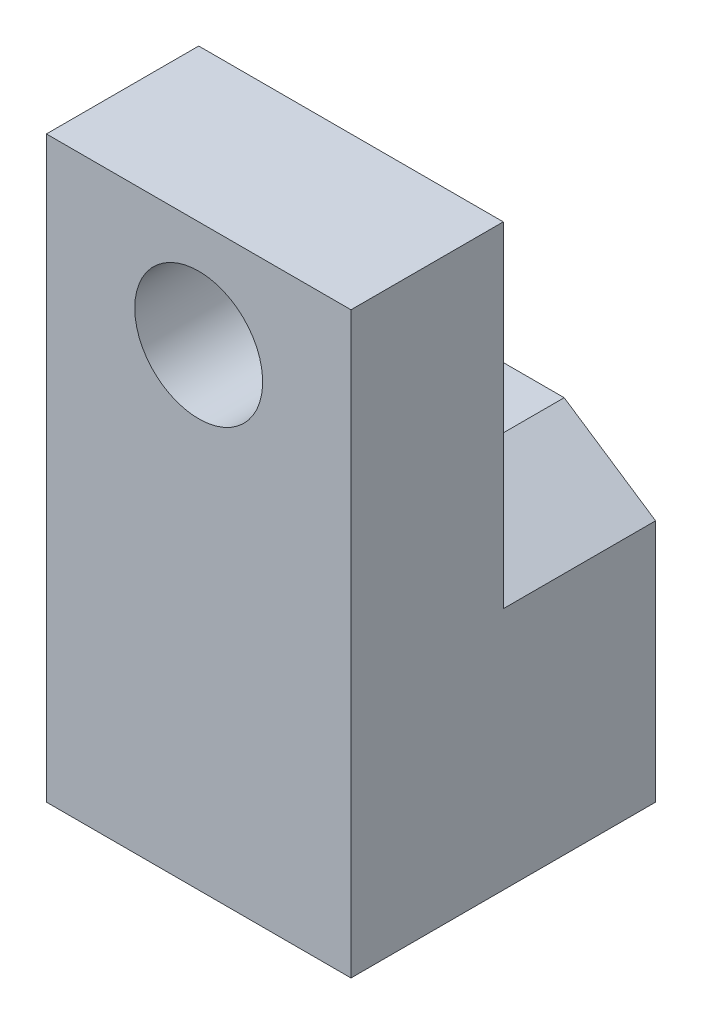
SolidWorks part; units mm, degrees
material "POM 乙缩醛共聚物"
ref_plane "前视基准面" through (0, 0, 0) normal (0, 0, 1) x (1, 0, 0)
ref_plane "上视基准面" through (0, 0, 0) normal (0, 1, 0) x (1, 0, 0)
ref_plane "右视基准面" through (0, 0, 0) normal (1, 0, 0) x (0, 0, -1)
sketch "草图1" plane through (0, 0, 0) normal (0, 0, 1) x (1, 0, 0)
  line L1 (-5, 9.5) -> (5, 9.5)
  line L2 (-5, 9.5) -> (-5, -9.5)
  line L3 (-5, -9.5) -> (5, -9.5)
  line L4 (5, 9.5) -> (5, -9.5)
  line L5 (-5, 9.5) -> (5, -9.5) construction
  line L6 (-5, -9.5) -> (5, 9.5) construction
  point P0 (0, 0)
  dimension "D1" = 10
  dimension "D2" = 19
extrude "凸台-拉伸1" add sketch "草图1" along normal blind 10
sketch "草图3" plane through (0, 0, 0) normal (0, 0, -1) x (-1, 0, 0)
  line L0 (0, 9.5) -> (0, -9.5) construction
  line L1 (-5, 9.5) -> (5, 9.5) construction
  line L2 (5, -9.5) -> (-5, -9.5) construction
  circle A0 centre (0, 6) radius 2.1
  dimension "D1" = 3.5
  dimension "D2" = 4.2
extrude "切除-拉伸2" cut sketch "草图3" against normal through all
sketch "草图6" plane through (0, 0, 0) normal (0, 0, -1) x (-1, 0, 0)
  line L0 (0, 9.5) -> (0, -9.5) construction
  line L1 (-5, 9.5) -> (5, 9.5) construction
  line L2 (5, -9.5) -> (-5, -9.5) construction
  line L3 (-5, -1.5) -> (-2, 0.5)
  line L4 (-2, 0.5) -> (2, 0.5)
  line L5 (-5, -9.5) -> (-5, 9.5)
  line L6 (-5, 9.5) -> (5, 9.5)
  line L7 (5, 9.5) -> (5, -9.5)
  line L8 (5, -1.5) -> (2, 0.5)
  point P18 (0, 0.5)
  dimension "D1" = 8
  dimension "D2" = 10
  dimension "D3" = 2
extrude "切除-拉伸4" cut sketch "草图6" against normal blind 5
sketch "草图2" plane through (0, -9.5, 0) normal (0, -1, 0) x (1, 0, 0)
  line L0 (0, 0) -> (0, 10) construction
  line L1 (-5, 10) -> (5, 10) construction
  circle A0 centre (0, 5) radius 1.5
  dimension "D1" = 3
extrude "切除-拉伸1" cut sketch "草图2" against normal blind 10
cosmetic thread "装饰螺纹线1" parameters "D1"=5, "D2"=9
